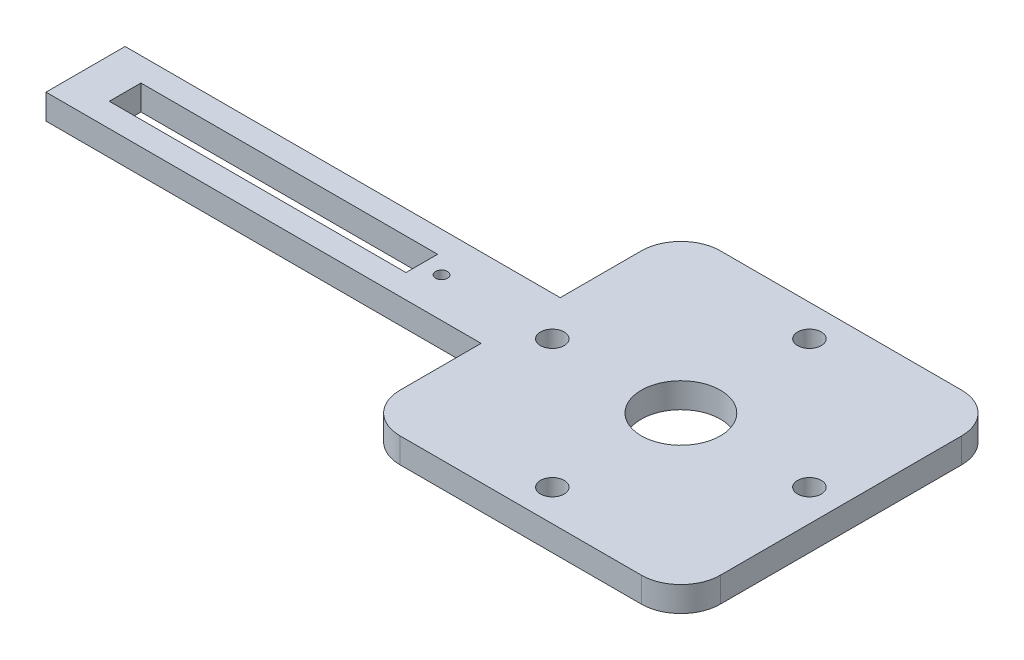
SolidWorks part; units mm, degrees
ref_plane "Front Plane" through (0, 0, 0) normal (0, 0, 1) x (1, 0, 0)
ref_plane "Top Plane" through (0, 0, 0) normal (0, 1, 0) x (1, 0, 0)
ref_plane "Right Plane" through (0, 0, 0) normal (1, 0, 0) x (0, 0, -1)
sketch "Sketch1" plane through (0, 0, 0) normal (0, 1, 0) x (1, 0, 0)
  line L0 (-40.5, 0) -> (-140.5, 0) construction
  line L1 (-40.5, 40.5) -> (40.5, 40.5)
  line L2 (-40.5, 40.5) -> (-40.5, 10)
  line L3 (-40.5, -40.5) -> (40.5, -40.5)
  line L4 (40.5, 40.5) -> (40.5, -40.5)
  line L5 (-40.5, 40.5) -> (40.5, -40.5) construction
  line L6 (-40.5, -40.5) -> (40.5, 40.5) construction
  line L7 (-40.5, -10) -> (-140.5, -10)
  line L8 (-40.5, 10) -> (-140.5, 10)
  line L9 (-40.5, 0) -> (0, 0) construction
  line L10 (-140.5, 0) -> (-65.5, 0) construction
  line L11 (-140.5, 4) -> (-65.5, 4) construction
  line L12 (-140.5, -4) -> (-65.5, -4) construction
  line L13 (-40.5, -10) -> (-40.5, -40.5)
  line L14 (-40.5, 10) -> (-40.5, -10) construction
  line L15 (-140.5, 10) -> (-140.5, -10) construction
  line L16 (-150.5, 0) -> (-140.5, 0) construction
  line L17 (0, 32.5) -> (0, 0) construction
  line L18 (0, 0) -> (32.5, 0) construction
  line L19 (-140.5, 10) -> (-150.5, 10)
  line L20 (0, -32.5) -> (0, 0) construction
  line L21 (-150.5, 10) -> (-150.5, -10)
  line L22 (-150.5, -10) -> (-140.5, -10)
  line L23 (-140.5, 4) -> (-140.5, -4)
  line L24 (-140.5, -4) -> (-65.5, -4)
  line L25 (-65.5, -4) -> (-65.5, 4)
  line L26 (-65.5, 4) -> (-140.5, 4)
  circle A0 centre (0, 0) radius 10
  circle A1 centre (0, 0) radius 32.5 construction
  circle A2 centre (0, 32.5) radius 3
  circle A3 centre (-32.5, 0) radius 3
  circle A4 centre (0, -32.5) radius 3
  circle A5 centre (32.5, 0) radius 3
  arc A7 (-140.5, 10) -> (-140.5, -10) centre (-140.5, 0) ccw construction
  arc A8 (-140.5, 4) -> (-140.5, -4) centre (-140.5, 0) ccw construction
  arc A9 (-65.5, -4) -> (-65.5, 4) centre (-65.5, 0) ccw construction
  circle A10 centre (-60.5, 0) radius 1.5
  point P17 (-90.5, 0)
  point P26 (-103, 0)
  dimension "D1" = 20
  dimension "D2" = 65
  dimension "D5" = 6
  dimension "D11" = 3
  dimension "D3" = 81
  dimension "D4" = 81
  dimension "D6" = 100
  dimension "D7" = 20
  dimension "D8" = 75
  dimension "D9" = 8
  dimension "D10" = 5
extrude "Boss-Extrude1" add sketch "Sketch1" along normal blind 6.35
fillet "Fillet1" radius 10 4 edges at (-40.5, 3.175, -40.5) (40.5, 3.175, -40.5) (40.5, 3.175, 40.5) (-40.5, 3.175, 40.5)
